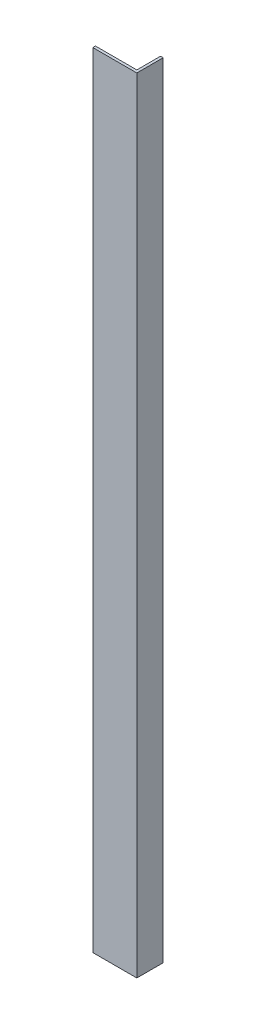
SolidWorks part; units mm, degrees
material "ASTM A36 Aço"
ref_plane "Plano frontal" through (0, 0, 0) normal (0, 0, 1) x (1, 0, 0)
ref_plane "Plano superior" through (0, 0, 0) normal (0, 1, 0) x (1, 0, 0)
ref_plane "Plano direito" through (0, 0, 0) normal (1, 0, 0) x (0, 0, -1)
sketch "Esboço3" plane through (0, 0, 0) normal (0, 1, 0) x (1, 0, 0)
  line L2 (-25, -12) -> (-25, -15)
  line L3 (-25, -15) -> (25, -15)
  line L4 (25, 15) -> (25, -15)
  line L6 (-22, -12) -> (22, -12)
  line L7 (22, 12) -> (22, -12)
  line L10 (22, 12) -> (22, 15)
  line L11 (22, 15) -> (25, 15)
  line L12 (-25, 15) -> (25, 15) construction
  line L13 (-22, 12) -> (22, 12) construction
  line L14 (-22, -12) -> (-25, -12)
  line L15 (-25, 15) -> (-25, -15) construction
  line L16 (-22, 12) -> (-22, -12) construction
  line L17 (20, -12) -> (25, -15) construction
  dimension "D1" = 50
  dimension "D2" = 30
  dimension "D3" = 3
extrude "Ressalto-extrusão2" add sketch "Esboço3" along normal blind 890
